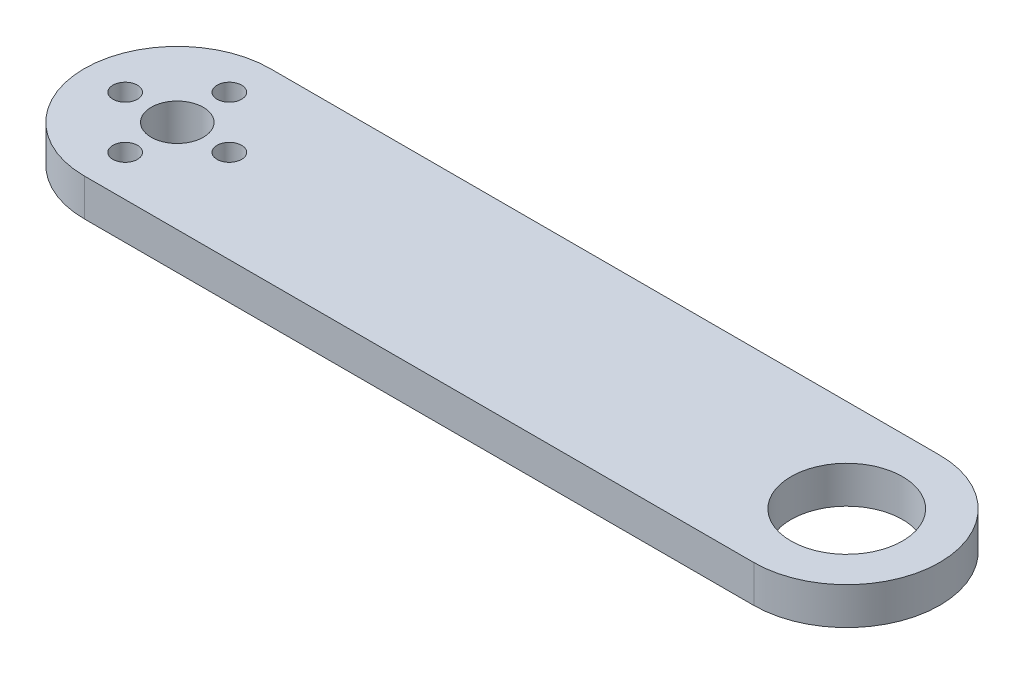
SolidWorks part; units mm, degrees
ref_plane "前视基准面" through (0, 0, 0) normal (0, 0, 1) x (1, 0, 0)
ref_plane "上视基准面" through (0, 0, 0) normal (0, 1, 0) x (1, 0, 0)
ref_plane "右视基准面" through (0, 0, 0) normal (1, 0, 0) x (0, 0, -1)
sketch "草图1" plane through (0, 0, 0) normal (0, 1, 0) x (1, 0, 0)
  line L0 (45, 0) -> (-45, 0) construction
  line L1 (45, -12.5) -> (-45, -12.5)
  line L2 (45, 12.5) -> (-45, 12.5)
  arc A0 (45, -12.5) -> (45, 12.5) centre (45, 0) ccw
  arc A1 (-45, 12.5) -> (-45, -12.5) centre (-45, 0) ccw
  point P2 (0, 0)
  dimension "D2" = 12.5
  dimension "D1" = 90
extrude "凸台-拉伸1" add sketch "草图1" along normal blind 5
sketch "草图2" plane through (0, 5, 0) normal (0, 1, 0) x (1, 0, 0)
  circle A0 centre (-45, 0) radius 3.5
  circle A1 centre (45, 0) radius 7.5
  circle A2 centre (-45, 0) radius 7 construction
  circle A3 centre (-45, 7) radius 1.65
  circle A4 centre (-38, 0) radius 1.65
  circle A5 centre (-45, -7) radius 1.65
  circle A6 centre (-52, 0) radius 1.65
  dimension "D1" = 7
  dimension "D2" = 14
  dimension "D3" = 3.3
  dimension "D4" = 15
extrude "切除-拉伸1" cut sketch "草图2" against normal up to next
